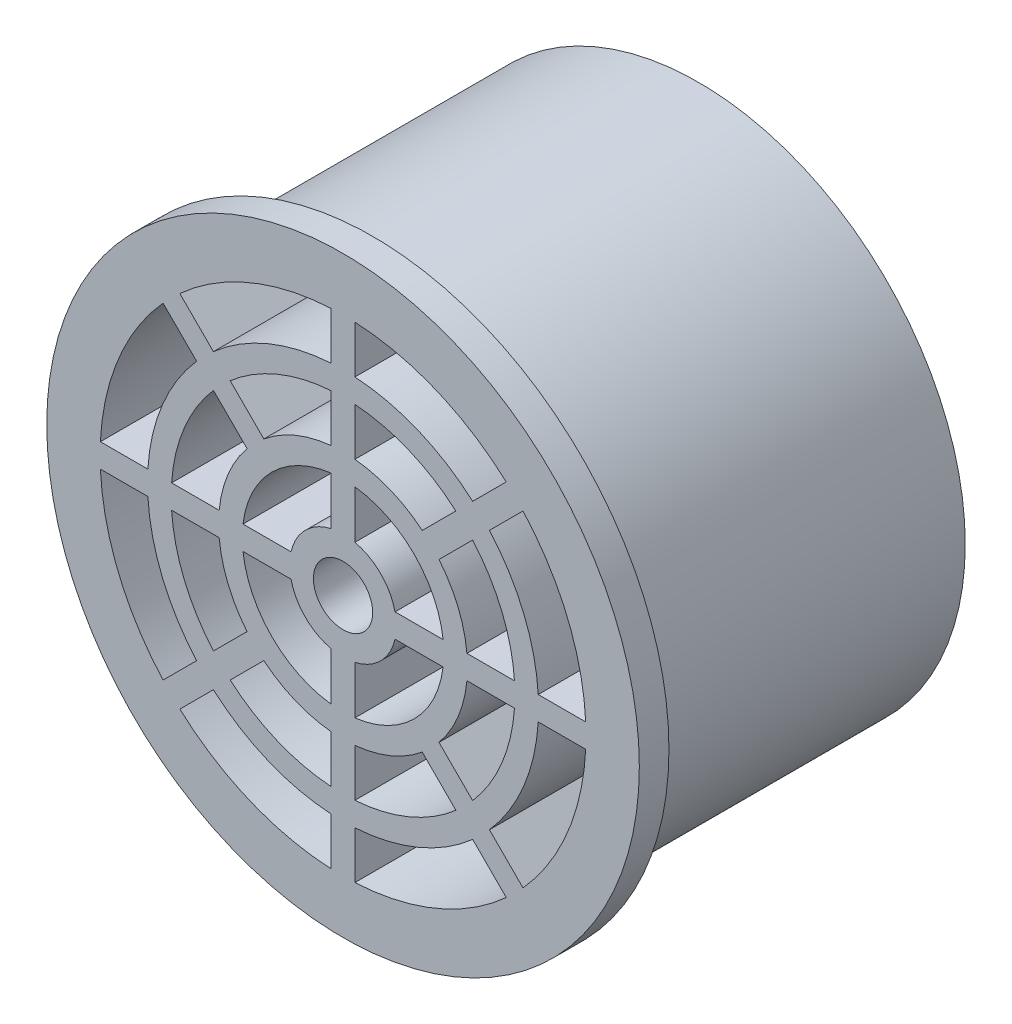
SolidWorks part; units mm, degrees
ref_plane "Front Plane" through (0, 0, 0) normal (0, 0, 1) x (1, 0, 0)
ref_plane "Top Plane" through (0, 0, 0) normal (0, 1, 0) x (1, 0, 0)
ref_plane "Right Plane" through (0, 0, 0) normal (1, 0, 0) x (0, 0, -1)
sketch "Sketch1" plane through (0, 0, 0) normal (0, 0, 1) x (1, 0, 0)
  circle A0 centre (0, 0) radius 10
  dimension "D1" = 20
extrude "Boss-Extrude1" add sketch "Sketch1" along normal blind 1 contours A0
sketch "Sketch2" plane through (0, 0, 0) normal (0, 0, -1) x (-1, 0, 0)
  circle A0 centre (0, 0) radius 9
  dimension "D1" = 18
extrude "Boss-Extrude2" add sketch "Sketch2" along normal blind 11
sketch "Sketch3" plane through (0, 0, 1) normal (0, 0, 1) x (1, 0, 0)
  line L0 (0, 9) -> (0, 6.6)
  line L1 (9, 0) -> (6.6, 0)
  line L2 (3.2392, 2.6735) -> (4.3743, 3.8086)
  line L3 (2.9698, 2.9698) -> (4.1012, 4.1012)
  line L4 (2.6735, 3.2392) -> (3.8086, 4.3743)
  line L5 (-2.6735, 3.2392) -> (-3.8086, 4.3743)
  line L6 (-3.2392, 2.6735) -> (-4.3743, 3.8086)
  line L7 (-3.2392, -2.6735) -> (-4.3743, -3.8086)
  line L8 (-2.9698, -2.9698) -> (-4.1012, -4.1012)
  line L9 (-2.6735, -3.2392) -> (-3.8086, -4.3743)
  line L10 (-0.4, 9) -> (-0.4, 6.5879)
  line L11 (9, 0.4) -> (6.5879, 0.4)
  line L12 (2.6735, -3.2392) -> (3.8086, -4.3743)
  line L13 (3.2392, -2.6735) -> (4.3743, -3.8086)
  line L14 (-4.1809, 0.4) -> (-5.7862, 0.4)
  line L15 (-4.2, 0) -> (-5.8, 0)
  line L16 (0.4, 9) -> (0.4, 6.5879)
  line L17 (9, -0.4) -> (6.5879, -0.4)
  line L18 (-2.9698, 2.9698) -> (-4.1012, 4.1012)
  line L19 (-4.1809, -0.4) -> (-5.7862, -0.4)
  line L20 (-0.4, -4.1809) -> (-0.4, -5.7862)
  line L21 (-0.4, 9) -> (-0.4, -9) construction
  line L22 (-0.3652, 0.9309) -> (-0.4, 0.9657)
  line L23 (0, -4.2) -> (0, -5.8)
  line L24 (0.4, -4.1809) -> (0.4, -5.7862)
  line L25 (0, 9) -> (0, -9) construction
  line L26 (0.3652, 0.9309) -> (0.4, 0.9657)
  line L27 (3.3764, -0.4) -> (0.9165, -0.4)
  line L28 (3.4, 0) -> (1, 0)
  line L29 (0.4, 9) -> (0.4, -9) construction
  line L30 (3.3764, 0.4) -> (0.9165, 0.4)
  line L31 (0.4, 3.3764) -> (0.4, 0.9165)
  line L32 (0, 3.4) -> (0, 1)
  line L33 (9, 0.4) -> (-9, 0.4) construction
  line L34 (0.9309, 0.3652) -> (0.9657, 0.4)
  line L35 (-0.4, 3.3764) -> (-0.4, 0.9165)
  line L36 (-4.3755, 4.9412) -> (-6.0811, 6.6468)
  line L37 (9, 0) -> (-9, 0) construction
  line L38 (0.9309, -0.3652) -> (0.9657, -0.4)
  line L39 (-4.6669, 4.6669) -> (-6.364, 6.364)
  line L40 (-4.9412, 4.3755) -> (-6.6468, 6.0811)
  line L41 (9, -0.4) -> (-9, -0.4) construction
  line L42 (2.9698, -2.9698) -> (4.1012, -4.1012)
  line L43 (-6.5879, 0.4) -> (-9, 0.4)
  line L44 (0.4, -0.9165) -> (0.4, -3.3764)
  line L45 (0.3652, -0.9309) -> (0.4, -0.9657)
  line L46 (-6.6, 0) -> (-9, 0)
  line L47 (0, -1) -> (0, -3.4)
  line L48 (-0.3652, -0.9309) -> (-0.4, -0.9657)
  line L49 (-6.5879, -0.4) -> (-9, -0.4)
  line L50 (-0.4, -0.9165) -> (-0.4, -3.3764)
  line L51 (-4.9412, -4.3755) -> (-6.6468, -6.0811)
  line L52 (-4.6669, -4.6669) -> (-6.364, -6.364)
  line L53 (-0.9165, -0.4) -> (-3.3764, -0.4)
  line L54 (-0.9309, -0.3652) -> (-0.9657, -0.4)
  line L55 (-4.3755, -4.9412) -> (-6.0811, -6.6468)
  line L56 (-1, 0) -> (-3.4, 0)
  line L57 (-0.9309, 0.3652) -> (-0.9657, 0.4)
  line L58 (4.3755, -4.9412) -> (6.0811, -6.6468)
  line L59 (-0.9165, 0.4) -> (-3.3764, 0.4)
  line L60 (4.6669, -4.6669) -> (6.364, -6.364)
  line L61 (-0.4, -6.5879) -> (-0.4, -9)
  line L62 (0, -6.6) -> (0, -9)
  line L63 (0.4, -6.5879) -> (0.4, -9)
  line L64 (4.9412, -4.3755) -> (6.6468, -6.0811)
  line L65 (5.7862, -0.4) -> (4.1809, -0.4)
  line L66 (5.8, 0) -> (4.2, 0)
  line L67 (5.7862, 0.4) -> (4.1809, 0.4)
  line L68 (4.9412, 4.3755) -> (6.6468, 6.0811)
  line L69 (4.6669, 4.6669) -> (6.364, 6.364)
  line L70 (4.3755, 4.9412) -> (6.0811, 6.6468)
  line L71 (0.4, 5.7862) -> (0.4, 4.1809)
  line L72 (0, 5.8) -> (0, 4.2)
  line L73 (-0.4, 5.7862) -> (-0.4, 4.1809)
  circle A0 centre (0, 0) radius 1
  circle A1 centre (0, 0) radius 1.8
  circle A2 centre (0, 0) radius 3.4
  circle A3 centre (0, 0) radius 4.2
  circle A4 centre (0, 0) radius 5.8
  circle A5 centre (0, 0) radius 6.6
  circle A6 centre (0, 0) radius 8.2
  circle A7 centre (0, 0) radius 9
  circle A8 centre (0, 0) radius 9
  point P16 (5.7983, 5.7983)
  point P21 (0, 0)
  dimension "D2" = 0.8
  dimension "D3" = 0.8
  dimension "D4" = 0.8
  dimension "D5" = 0.8
  dimension "D6" = 1.6
  dimension "D7" = 1.6
  dimension "D8" = 1.6
  dimension "D10" = 0.4
  dimension "D1" = 0
  dimension "D11" = 0.4
extrude "Cut-Extrude2" cut sketch "Sketch3" against normal through all contours A0 | L35 A2 L59 A1 | L30 A2 L31 A1 | L44 A2 L27 A1 | L53 A2 L50 A1 | L4 A4 L71 A3 | L73 A4 L5 A3 | L6 A4 L14 A3 | L19 A4 L7 A3 | L9 A4 L20 A3 | L24 A4 L12 A3 | L13 A4 L65 A3 | L67 A4 L2 A3 | L11 A6 L68 A5 | L70 A6 L16 A5 | L10 A6 L36 A5 | L40 A6 L43 A5 | L49 A6 L51 A5 | L55 A6 L61 A5 | L63 A6 L58 A5 | L64 A6 L17 A5
